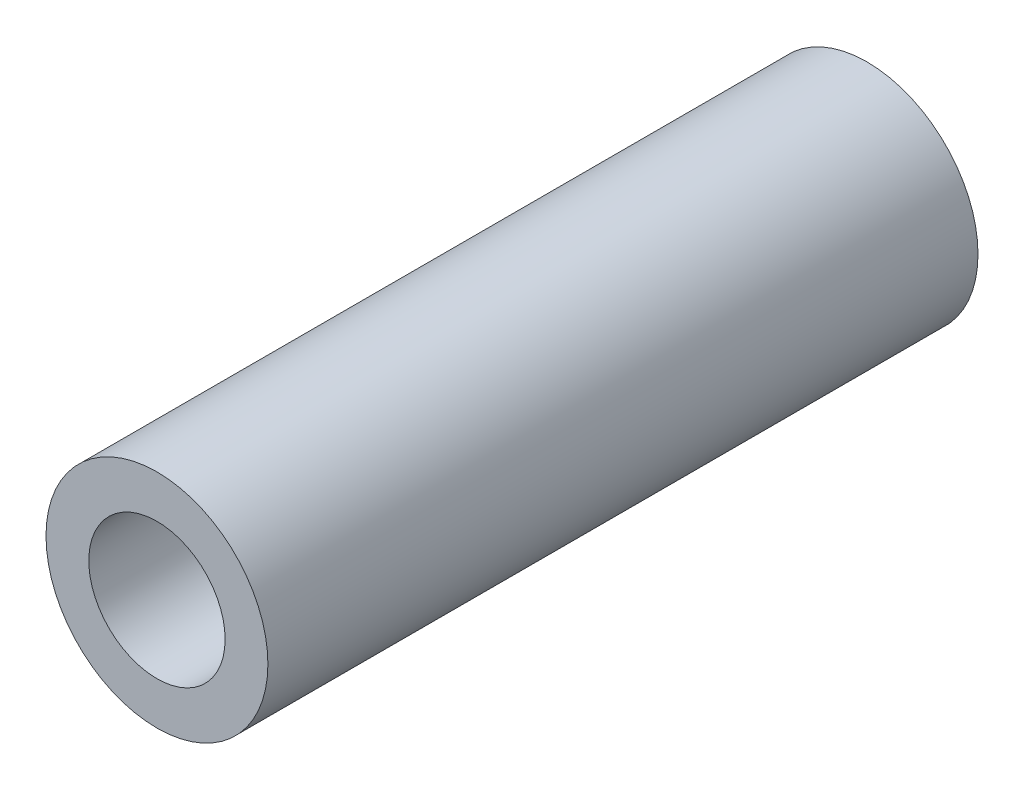
SolidWorks part; units mm, degrees
ref_plane "Front Plane" through (0, 0, 0) normal (0, 0, 1) x (1, 0, 0)
ref_plane "Top Plane" through (0, 0, 0) normal (0, 1, 0) x (1, 0, 0)
ref_plane "Right Plane" through (0, 0, 0) normal (1, 0, 0) x (0, 0, -1)
sketch "Sketch1" plane through (0, 0, 0) normal (0, 0, 1) x (1, 0, 0)
  circle A0 centre (0, 0) radius 3.9688
  circle A1 centre (0, 0) radius 2.4384
  dimension "OD" = 7.9375
  dimension "ID" = 4.8768
extrude "Extrude1" add sketch "Sketch1" along normal mid plane 25.4
sketch "Sketch2" plane through (0, 0, 0) normal (1, 0, 0) x (0, 0, -1)
  line L0 (-12.7, -2.4384) -> (12.7, -2.4384) construction
  line L3 (12.7, 2.4384) -> (-12.7, 2.4384) construction
  line L5 (-12.7, -2.4384) -> (12.7, -2.4384)
  line L6 (12.7, 2.4384) -> (-12.7, 2.4384)
sketch "Sketch4" plane through (0, 0, 12.7) normal (0, 0, 1) x (1, 0, 0)
  line L0 (0, 0) -> (-1.7242, 1.7242)
  line L1 (0, -2.1828) -> (0, 2.1828) construction
  circle A0 centre (0, 0) radius 2.4384 construction
  dimension "D1" = 45
